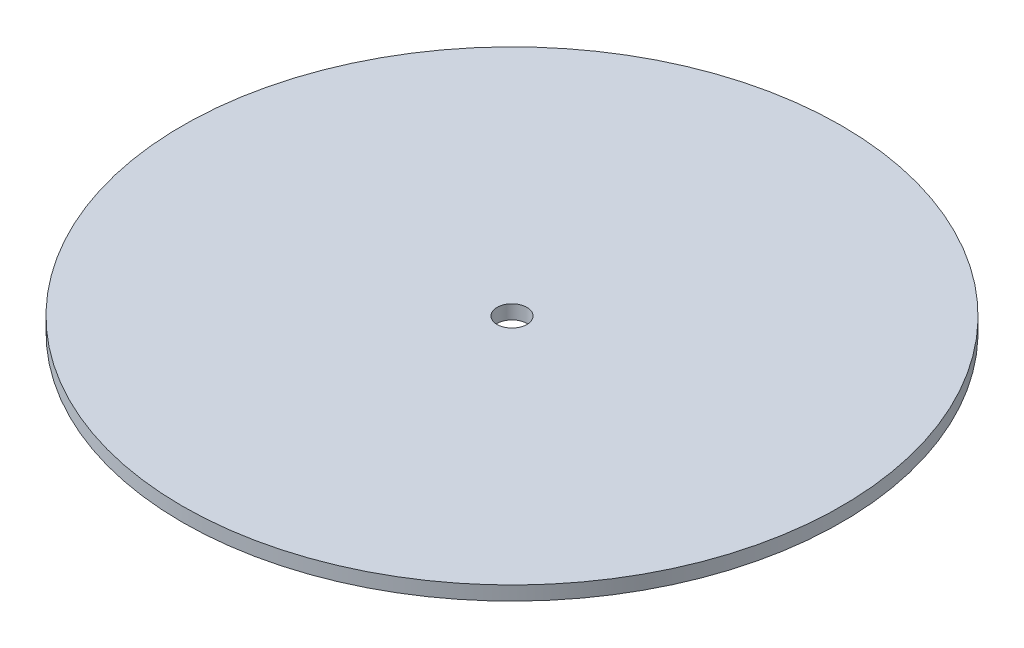
SolidWorks part; units mm, degrees
ref_plane "Front Plane" through (0, 0, 0) normal (0, 0, 1) x (1, 0, 0)
ref_plane "Top Plane" through (0, 0, 0) normal (0, 1, 0) x (1, 0, 0)
ref_plane "Right Plane" through (0, 0, 0) normal (1, 0, 0) x (0, 0, -1)
sketch "Sketch1" plane through (0, 0, 0) normal (0, 1, 0) x (1, 0, 0)
  circle A0 centre (0, 0) radius 74.7776
  dimension "D1" = 149.5552
extrude "Boss-Extrude1" add sketch "Sketch1" along normal blind 3.175
hole_wizard "1/4 Clearance Hole1" positions "Sketch2" profile "Sketch4" hole size "1/4" standard "ANSI Inch" end condition through all
sketch "Sketch2" plane through (0, 3.175, 0) normal (0, 1, 0) x (1, 0, 0)
  point P0 (0, 0)
sketch "Sketch4" plane through (0, 3.175, 0) normal (1, 0, 0) x (0, 0, 1)
  line L0 (0, 0) -> (0, 3.175)
  line L1 (0, 3.175) -> (3.3782, 3.175)
  line L2 (3.3782, 3.175) -> (3.3782, 0)
  line L5 (3.3782, 0) -> (0, 0)
  line L11 (0, -6.35) -> (0, 107.95) construction
  dimension "Thru Hole Dia." = 6.7564
  dimension "Thru Hole Depth" = 3.175
equation "\"airframeInnerDiameter\"= 6in"
equation "\"outerDiameter\"= 6.112in"
equation "\"airframeBulkheadThickness\"= 0.125in"
equation "\"payloadAirframeLength\"= 10in"
equation "\"payloadInnerDiameter\"= 6in - 0.056in"
equation "\"payloadOuterDiameter\"= \"airframeInnerDiameter\""
equation "\"payloadLength\"= 11in"
equation "\"payloadBand\"= 2in"
equation "\"payloadOffsetFromAft\"= 6in"
equation "\"upperAirframeLength\"= 25in"
equation "\"recoveryBayInnerDiameter\"= 5.888in"
equation "\"recoveryLength\"= 8in"
equation "\"recoveryBand\"= 2in"
equation "\"recoveryCouplerOuter\"=\"airframeInnerDiameter\""
equation "\"recoveryOffsetFromAft\"= 3in"
equation "\"midAirframeLength\"= 20in"
equation "\"atsLength\"= 11in"
equation "\"atsInner\"= 5.888in"
equation "\"atsBand\"= 2in"
equation "\"atsCouplerOuter\"=\"airframeInnerDiameter\""
equation "\"atsOffsetFromAft\"= 3in"
equation "\"lowerAirframeLength\"= 40in"
equation "\"motorTubeOuterDiameter\"= 4.25in"
equation "\"motorTubeInnerDiameter\"= 4in"
equation "\"motorTubeLength\"= 32in"
equation "\"centeringRingOuterDiameter\"= \"airframeInnerDiameter\""
equation "\"centeringRingInnerDiameter\"= \"motorTubeOuterDiameter\""
equation "\"centeringRingThickness\"= 0.375in"
equation "\"topCenteringRingOffsetFromAft\"= 16.7in"
equation "\"bottomCenteringRingOffsetFromAft\"= 0.3in"
equation "\"finSlotLength\"= 8in"
equation "\"finSlotOffsetFromAft\"= 3in"
equation "\"finSlotWidth\"= 0.187in"
equation "\"motorCasingOuterDiameter\"= 3in"
equation "\"motorCasingCenteringRingThickness\"= 0.25in"
equation "\"D1@Sketch1\" = \"recoveryBayInnerDiameter\""
equation "\"D1@Boss-Extrude1\"=\"airframeBulkheadThickness\""
